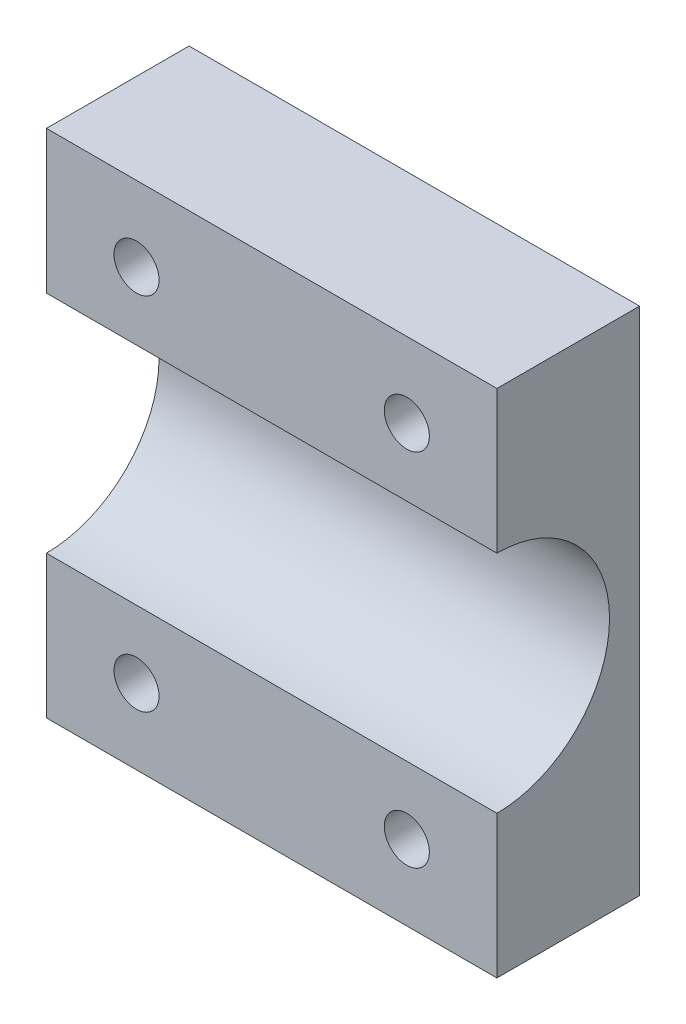
SolidWorks part; units mm, degrees
ref_plane "前视基准面" through (0, 0, 0) normal (0, 0, 1) x (1, 0, 0)
ref_plane "上视基准面" through (0, 0, 0) normal (0, 1, 0) x (1, 0, 0)
ref_plane "右视基准面" through (0, 0, 0) normal (1, 0, 0) x (0, 0, -1)
sketch "草图1" plane through (0, 0, 0) normal (0, 0, 1) x (1, 0, 0)
  line L0 (-22.961, 17) -> (7.039, -17) construction
  line L1 (-22.961, 17) -> (7.039, 17)
  line L2 (-22.961, 17) -> (-22.961, -17)
  line L3 (-22.961, -17) -> (7.039, -17)
  line L4 (7.039, 17) -> (7.039, -17)
  line L10 (-16.961, 12) -> (1.039, -12) construction
  line L11 (-16.961, -12) -> (1.039, 12) construction
  circle A0 centre (1.039, 12) radius 1.5
  circle A1 centre (-16.961, 12) radius 1.5
  circle A2 centre (1.039, -12) radius 1.5
  circle A3 centre (-16.961, -12) radius 1.5
  point P4 (-7.961, 0)
  dimension "D1" = 34
  dimension "D2" = 30
  dimension "D3" = 18
  dimension "D4" = 24
extrude "凸台-拉伸2" add sketch "草图1" along normal blind 9.5
sketch "草图2" plane through (0, 17, 0) normal (0, 1, 0) x (1, 0, 0)
  line L0 (-22.961, -9.5) -> (7.039, -9.5) construction
  circle A0 centre (-7.961, -9.5) radius 7.5
sketch "草图3" plane through (-22.961, 0, 0) normal (-1, 0, 0) x (0, 0, 1)
  line L0 (9.5, -17) -> (9.5, 17) construction
  circle A0 centre (9.5, 0) radius 7.5
extrude "切除-拉伸1" cut sketch "草图3" against normal blind 40
